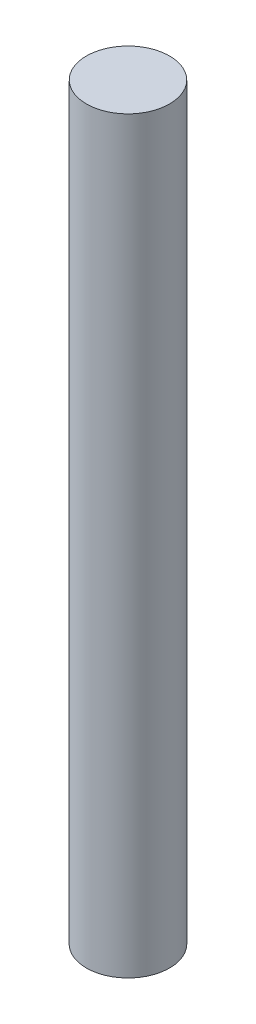
SolidWorks part; units mm, degrees
ref_plane "前视基准面" through (0, 0, 0) normal (0, 0, 1) x (1, 0, 0)
ref_plane "上视基准面" through (0, 0, 0) normal (0, 1, 0) x (1, 0, 0)
ref_plane "右视基准面" through (0, 0, 0) normal (1, 0, 0) x (0, 0, -1)
sketch "草图1" plane through (0, 0, 0) normal (0, 1, 0) x (1, 0, 0)
  circle A0 centre (0, 0) radius 30
  dimension "D1" = 60
extrude "凸台-拉伸1" add sketch "草图1" along normal blind 540
